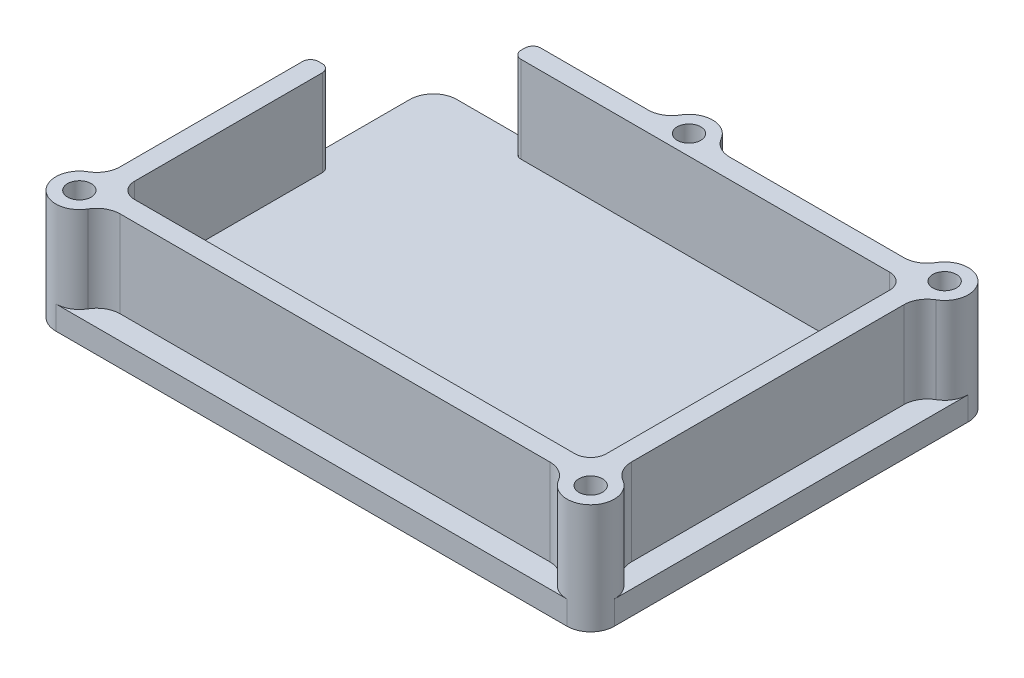
SolidWorks part; units mm, degrees
material "ABS"
ref_plane "Front Plane" through (0, 0, 0) normal (0, 0, 1) x (1, 0, 0)
ref_plane "Top Plane" through (0, 0, 0) normal (0, 1, 0) x (1, 0, 0)
ref_plane "Right Plane" through (0, 0, 0) normal (1, 0, 0) x (0, 0, -1)
sketch "Sketch5" plane through (0, 0, 0) normal (0, 1, 0) x (1, 0, 0)
  line L0 (-35, -25) -> (-35, 25) construction
  line L1 (-30, -20) -> (30, -20) construction
  line L2 (-30, -20) -> (-30, 20) construction
  line L3 (-30, 20) -> (30, 20) construction
  line L4 (30, -20) -> (30, 20) construction
  line L5 (-30, -20) -> (30, 20) construction
  line L6 (-30, 20) -> (30, -20) construction
  line L7 (-35, 25) -> (35, 25) construction
  line L8 (35, -25) -> (35, 25) construction
  line L9 (-35, -25) -> (35, -25) construction
  line L10 (-5.1962, 22.5) -> (-29.5, 22.5)
  line L14 (-32.5, 19.5) -> (-32.5, -17.3038)
  line L15 (31.2667, 21.6462) -> (-32.5, -22.5) construction
  line L16 (31.2667, -21.6462) -> (-32.5, 22.5) construction
  line L20 (-32.5, 9.9079) -> (-30, 9.9079)
  line L25 (-32.5, -25.5) -> (32.5, -25.5)
  line L26 (35.5, -22.5) -> (35.5, 22.5)
  line L27 (32.5, 25.5) -> (0, 25.5)
  arc A1 (35.5, 22.5) -> (32.5, 25.5) centre (32.5, 22.5) ccw
  arc A2 (32.5, -25.5) -> (35.5, -22.5) centre (32.5, -22.5) ccw
  arc A3 (-34, -19.9019) -> (-32.5, -25.5) centre (-32.5, -22.5) ccw
  circle A4 centre (0, 22.5) radius 1.5
  circle A5 centre (32.5, 22.5) radius 1.5
  circle A6 centre (32.5, -22.5) radius 1.5
  circle A7 centre (-32.5, -22.5) radius 1.5
  arc A8 (0, 25.5) -> (-2.5981, 24) centre (0, 22.5) ccw
  arc A9 (-29.5, 22.5) -> (-32.5, 19.5) centre (-29.5, 19.5) ccw
  arc A10 (-32.5, -17.3038) -> (-34, -19.9019) centre (-35.5, -17.3038) cw
  arc A11 (-2.5981, 24) -> (-5.1962, 22.5) centre (-5.1962, 25.5) cw
  point P0 (0, 0)
  point P10 (0, 0)
  point P16 (0, 0)
  dimension "D7" = 6
  dimension "D8" = 6
  dimension "D9" = 6
  dimension "D10" = 3
  dimension "D11" = 3
  dimension "D12" = 3
  dimension "D13" = 3
  dimension "D5" = 3
  dimension "D1" = 40
  dimension "D2" = 60
  dimension "D4" = 2.5
  dimension "D3" = 5
extrude "Boss-Extrude2" add sketch "Sketch5" along normal blind 3
sketch "Sketch6" plane through (0, 3, 0) normal (0, 1, 0) x (1, 0, 0)
  line L0 (-32.5, 5.8851) -> (-32.5, -17.3038)
  line L1 (28, 20) -> (-18.8542, 20)
  line L2 (30, 18) -> (30, -18)
  line L3 (28, -20) -> (-28, -20)
  line L4 (-30, 5.8851) -> (-30, -18)
  line L5 (30, 20) -> (-30, -20) construction
  line L6 (30, -20) -> (0, 0) construction
  line L8 (32.5, 17.3038) -> (32.5, -17.3038)
  line L10 (27.3038, 22.5) -> (5.1962, 22.5)
  line L11 (27.3038, -22.5) -> (-27.3038, -22.5)
  line L12 (-5.1962, 22.5) -> (-18.8542, 22.5)
  line L13 (-31.5, 6.8851) -> (-31, 6.8851)
  line L14 (-19.8542, 21) -> (-19.8542, 21.5)
  line L15 (-29.2911, 19.5274) -> (-30, 20) construction
  arc A0 (-5.1962, 22.5) -> (-2.5981, 24) centre (-5.1962, 25.5) ccw construction
  arc A1 (-34, -19.9019) -> (-32.5, -17.3038) centre (-35.5, -17.3038) ccw construction
  arc A2 (-5.1962, 22.5) -> (-2.5981, 24) centre (-5.1962, 25.5) ccw
  arc A3 (-34, -19.9019) -> (-32.5, -17.3038) centre (-35.5, -17.3038) ccw
  arc A4 (-34, -19.9019) -> (-29.9019, -24) centre (-32.5, -22.5) ccw
  arc A6 (34, 19.9019) -> (29.9019, 24) centre (32.5, 22.5) ccw
  arc A7 (29.9019, -24) -> (34, -19.9019) centre (32.5, -22.5) ccw
  arc A8 (2.5981, 24) -> (-2.5981, 24) centre (0, 22.5) ccw
  circle A9 centre (0, 22.5) radius 1.5
  circle A10 centre (32.5, 22.5) radius 1.5
  circle A11 centre (32.5, -22.5) radius 1.5
  circle A12 centre (-32.5, -22.5) radius 1.5
  arc A15 (-27.3038, -22.5) -> (-29.9019, -24) centre (-27.3038, -25.5) ccw
  arc A16 (32.5, -17.3038) -> (34, -19.9019) centre (35.5, -17.3038) ccw
  arc A17 (27.3038, -22.5) -> (29.9019, -24) centre (27.3038, -25.5) cw
  arc A18 (34, 19.9019) -> (32.5, 17.3038) centre (35.5, 17.3038) ccw
  arc A19 (29.9019, 24) -> (27.3038, 22.5) centre (27.3038, 25.5) cw
  arc A20 (2.5981, 24) -> (5.1962, 22.5) centre (5.1962, 25.5) ccw
  arc A21 (-28, -20) -> (-30, -18) centre (-28, -18) cw
  arc A22 (30, -18) -> (28, -20) centre (28, -18) cw
  arc A23 (28, 20) -> (30, 18) centre (28, 18) cw
  arc A25 (-19.8542, 21.5) -> (-18.8542, 22.5) centre (-18.8542, 21.5) cw
  arc A26 (-19.8542, 21) -> (-18.8542, 20) centre (-18.8542, 21) ccw
  arc A27 (-31, 6.8851) -> (-30, 5.8851) centre (-31, 5.8851) cw
  arc A28 (-31.5, 6.8851) -> (-32.5, 5.8851) centre (-31.5, 5.8851) ccw
  point P0 (0, 0)
  dimension "D3" = 3
  dimension "D4" = 2
  dimension "D5" = 1
  dimension "D1" = 40
  dimension "D2" = 60
extrude "Boss-Extrude3" add sketch "Sketch6" along normal blind 11
